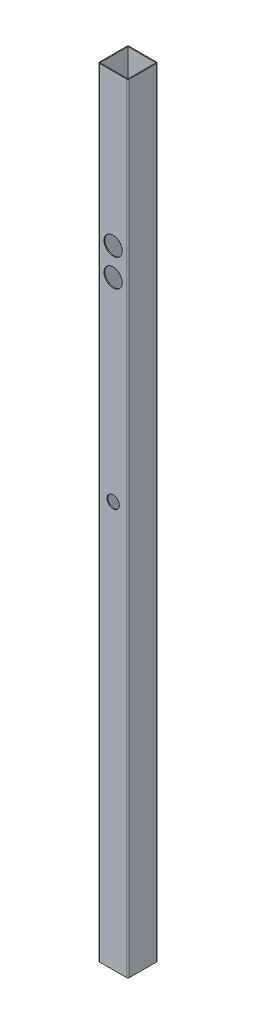
SolidWorks part; units mm, degrees
material "AISI 316 Stainless Steel Sheet (SS)"
ref_plane "Front Plane" through (0, 0, 0) normal (0, 0, 1) x (1, 0, 0)
ref_plane "Top Plane" through (0, 0, 0) normal (0, 1, 0) x (1, 0, 0)
ref_plane "Right Plane" through (0, 0, 0) normal (1, 0, 0) x (0, 0, -1)
sketch "Sketch1" plane through (0, 0, 0) normal (0, 1, 0) x (1, 0, 0)
  line L0 (-30.5, 30.5) -> (30.5, 30.5)
  line L1 (-32.5, 32.5) -> (32.5, 32.5)
  line L2 (-32.5, 32.5) -> (-32.5, -32.5)
  line L3 (-32.5, -32.5) -> (32.5, -32.5)
  line L4 (32.5, 32.5) -> (32.5, -32.5)
  line L5 (-32.5, 32.5) -> (32.5, -32.5) construction
  line L6 (-32.5, -32.5) -> (32.5, 32.5) construction
  line L7 (30.5, 30.5) -> (30.5, -30.5)
  line L8 (-30.5, -30.5) -> (30.5, -30.5)
  line L9 (-30.5, 30.5) -> (-30.5, -30.5)
  point P0 (0, 0)
  dimension "D1" = 65
  dimension "D2" = 65
  dimension "D3" = 2
extrude "Boss-Extrude1" add sketch "Sketch1" along normal blind 1700
sketch "Sketch2" plane through (0, 0, -32.5) normal (0, 0, -1) x (-1, 0, 0)
  line L0 (-32.5, 0) -> (32.5, 0) construction
  line L1 (0, 1274.2328) -> (0, 815.3858) construction
  line L2 (32.5, 1700) -> (-32.5, 1700) construction
  line L4 (-20, 1340) -> (20, 1340) construction
  line L5 (-20, 1340) -> (-20, 1400) construction
  line L6 (-20, 1400) -> (20, 1400) construction
  line L7 (20, 1340) -> (20, 1400) construction
  line L8 (-20, 1340) -> (20, 1400) construction
  line L9 (-20, 1400) -> (20, 1340) construction
  circle A0 centre (20, 1400) radius 3
  circle A1 centre (-20, 1400) radius 3
  circle A2 centre (20, 1340) radius 3
  circle A3 centre (-20, 1340) radius 3
  circle A4 centre (-20, 1280) radius 3
  circle A5 centre (20, 1280) radius 3
  circle A6 centre (0, 300) radius 27.5
  point P4 (0, 1370)
  dimension "D1" = 40
  dimension "D2" = 300
  dimension "D3" = 60
  dimension "D4" = 6
  dimension "D5" = 55
  dimension "D6" = 300
extrude "Cut-Extrude1" cut sketch "Sketch2" against normal up to next
fillet "Fillet1" radius 3 4 edges at (-32.5, 850, -32.5) (-32.5, 850, 32.5) (32.5, 850, 32.5) (32.5, 850, -32.5)
sketch "Sketch3" plane through (0, 0, 32.5) normal (0, 0, 1) x (1, 0, 0)
  line L0 (20, 1400) -> (-20, 1340) construction
  line L1 (-20, 1340) -> (20, 1280) construction
  line L2 (20, 1280) -> (-20, 1280) construction
  line L3 (-20, 1280) -> (20, 1340) construction
  line L4 (20, 1340) -> (-20, 1400) construction
  circle A0 centre (0, 1370) radius 20
  circle A1 centre (0, 1310) radius 20
  dimension "D1" = 40
extrude "Cut-Extrude2" cut sketch "Sketch3" against normal up to next
sketch "Sketch4" plane through (0, 0, -32.5) normal (0, 0, -1) x (-1, 0, 0)
  line L1 (0, 872) -> (0, 723.1675) construction
  line L7 (0, 923) -> (0, 873) construction
  line L9 (0, 923) -> (0, 873) construction
  circle A0 centre (0, 885.5) radius 13.5
  dimension "D3" = 27
extrude "Cut-Extrude3" cut sketch "Sketch4" against normal through all
